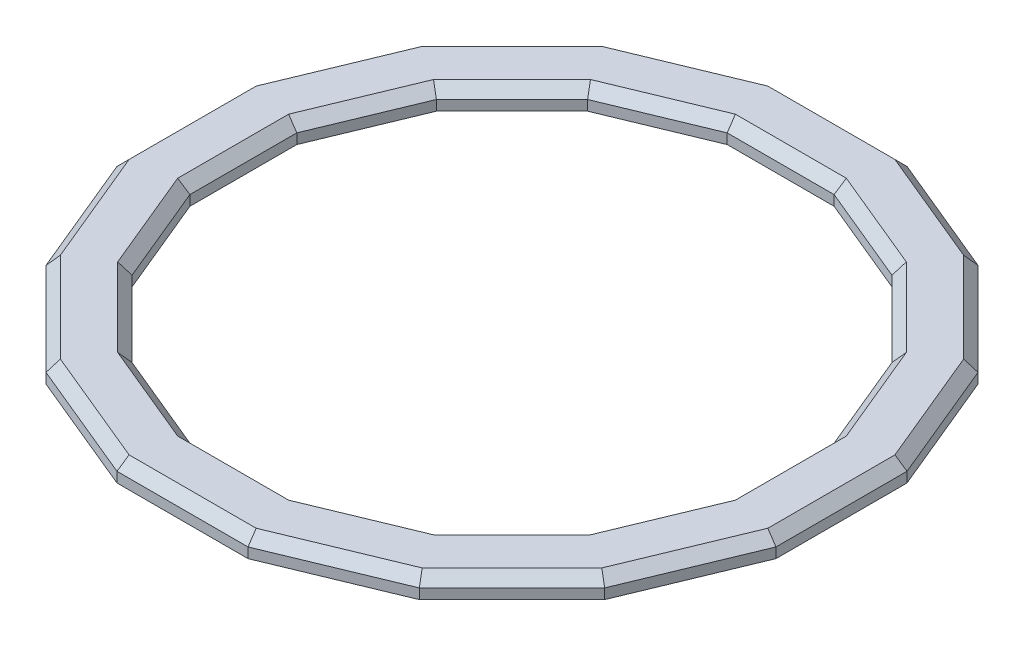
SolidWorks part; units mm, degrees
ref_plane "Front Plane" through (0, 0, 0) normal (0, 0, 1) x (1, 0, 0)
ref_plane "Top Plane" through (0, 0, 0) normal (0, 1, 0) x (1, 0, 0)
ref_plane "Right Plane" through (0, 0, 0) normal (1, 0, 0) x (0, 0, -1)
sketch "Sketch1" plane through (0, 0, 0) normal (0, 1, 0) x (1, 0, 0)
  line L1 (36.8195, 55.1043) -> (12.9293, 65)
  line L2 (12.9293, 65) -> (-12.9293, 65)
  line L3 (-12.9293, 65) -> (-36.8195, 55.1043)
  line L4 (-36.8195, 55.1043) -> (-55.1043, 36.8195)
  line L5 (-55.1043, 36.8195) -> (-65, 12.9293)
  line L6 (-65, 12.9293) -> (-65, -12.9293)
  line L7 (-65, -12.9293) -> (-55.1043, -36.8195)
  line L8 (-55.1043, -36.8195) -> (-36.8195, -55.1043)
  line L9 (-36.8195, -55.1043) -> (-12.9293, -65)
  line L10 (-12.9293, -65) -> (12.9293, -65)
  line L11 (12.9293, -65) -> (36.8195, -55.1043)
  line L12 (36.8195, -55.1043) -> (55.1043, -36.8195)
  line L13 (55.1043, -36.8195) -> (65, -12.9293)
  line L14 (65, -12.9293) -> (65, 12.9293)
  line L15 (65, 12.9293) -> (55.1043, 36.8195)
  line L16 (55.1043, 36.8195) -> (36.8195, 55.1043)
  line L17 (10.5424, 53) -> (-10.5424, 53)
  line L18 (-10.5424, 53) -> (-30.0221, 44.9312)
  line L19 (-30.0221, 44.9312) -> (-44.9312, 30.0221)
  line L20 (-44.9312, 30.0221) -> (-53, 10.5424)
  line L21 (-53, 10.5424) -> (-53, -10.5424)
  line L22 (-53, -10.5424) -> (-44.9312, -30.0221)
  line L23 (-44.9312, -30.0221) -> (-30.0221, -44.9312)
  line L24 (-30.0221, -44.9312) -> (-10.5424, -53)
  line L25 (-10.5424, -53) -> (10.5424, -53)
  line L26 (10.5424, -53) -> (30.0221, -44.9312)
  line L27 (30.0221, -44.9312) -> (44.9312, -30.0221)
  line L28 (44.9312, -30.0221) -> (53, -10.5424)
  line L29 (53, -10.5424) -> (53, 10.5424)
  line L30 (53, 10.5424) -> (44.9312, 30.0221)
  line L31 (44.9312, 30.0221) -> (30.0221, 44.9312)
  line L32 (30.0221, 44.9312) -> (10.5424, 53)
  circle A0 centre (0, 0) radius 65 construction
  circle A1 centre (0, 0) radius 53 construction
  dimension "D1" = 130
  dimension "D2" = 12
extrude "Boss-Extrude1" add sketch "Sketch1" along normal blind 4
chamfer "Chamfer1" distance 2 angle 45 32 edges at (-20.2822, 4, -48.9656) (-37.4767, 4, -37.4767) (-48.9656, 4, -20.2822) (-53, 4, 0) (-48.9656, 4, 20.2822) (-37.4767, 4, 37.4767) (-20.2822, 4, 48.9656) (0, 4, 53) (20.2822, 4, 48.9656) (37.4767, 4, 37.4767) (48.9656, 4, 20.2822) (53, 4, 0) (48.9656, 4, -20.2822) (37.4767, 4, -37.4767) (20.2822, 4, -48.9656) (0, 4, -53) (60.0522, 4, -24.8744) (65, 4, 0) (60.0522, 4, 24.8744) (45.9619, 4, 45.9619) (24.8744, 4, 60.0522) (0, 4, 65) (-24.8744, 4, 60.0522) (-45.9619, 4, 45.9619) (-60.0522, 4, 24.8744) (-65, 4, 0) (-60.0522, 4, -24.8744) (-45.9619, 4, -45.9619) (-24.8744, 4, -60.0522) (0, 4, -65) (24.8744, 4, -60.0522) (45.9619, 4, -45.9619)
shell "Shell1" thickness 2
